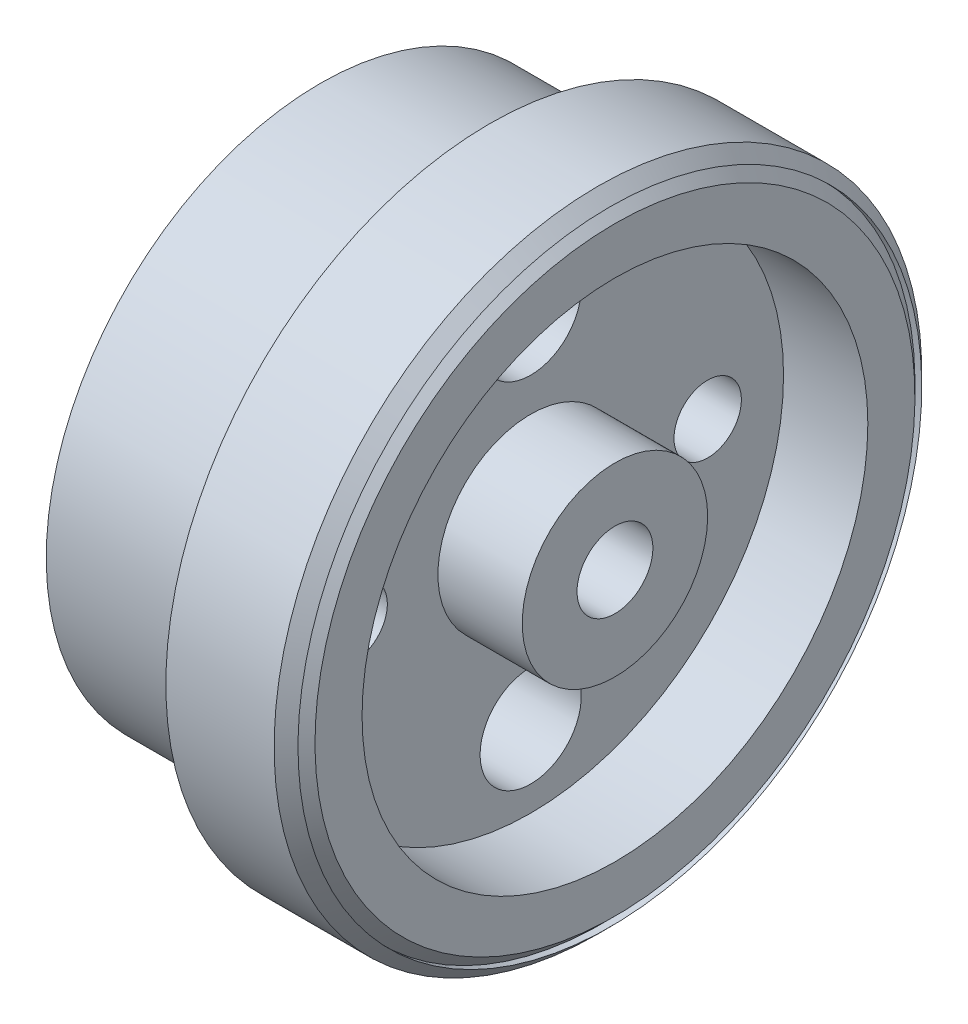
SolidWorks part; units mm, degrees
material "Erable"
ref_plane "Plan de face" through (0, 0, 0) normal (0, 0, 1) x (1, 0, 0)
ref_plane "Plan de dessus" through (0, 0, 0) normal (0, 1, 0) x (1, 0, 0)
ref_plane "Plan de droite" through (0, 0, 0) normal (1, 0, 0) x (0, 0, -1)
sketch "Esquisse1" plane through (0, 0, 0) normal (0, 0, 1) x (1, 0, 0)
  line L0 (0, 0) -> (-42.1873, 0) construction
  line L2 (-0.6031, -37) -> (-1.4142, -37)
  line L40 (-1.4142, -37) -> (0, -35.5858)
  line L55 (-0.6031, -37) -> (-2.0173, -38.4142)
  line L56 (-2.0173, -38.4142) -> (-14.8625, -38.4142)
  line L57 (-14.8625, -38.4142) -> (-15.958, -36.7409)
  line L82 (0, -4.5) -> (0, -35.5858)
  line L83 (-15.958, -36.7409) -> (-15.958, -32.5076)
  line L84 (-15.958, -32.5076) -> (-34.958, -32.5076)
  line L85 (-34.958, -32.5076) -> (-34.958, -27.5104)
  line L89 (-34.958, -15.3377) -> (-34.958, -11.0143)
  line L90 (-34.958, -11.0143) -> (-36.958, -11.0143)
  line L91 (-36.958, -11.0143) -> (-36.958, -11)
  line L92 (-36.958, -11) -> (-44.958, -11)
  line L94 (-14.8625, -38.4142) -> (-14.8625, -28.5496) construction
  line L96 (-34.958, -27.5104) -> (-34.958, -15.3377)
  line L103 (-43.429, -7.5149) -> (-44.958, -8.8042)
  line L104 (-44.958, -8.8042) -> (-44.958, -11)
  line L105 (-23.429, -7.5149) -> (-20.4142, -4.5)
  line L106 (-43.429, -7.5149) -> (-3.9293, -7.5149) construction
  line L107 (-43.429, -7.5149) -> (-23.429, -7.5149)
  line L108 (0, -4.5) -> (-20.4142, -4.5)
  dimension "D2" = 2
  dimension "D3" = 2
  dimension "D4" = 19
  dimension "D5" = 2
  dimension "D6" = 12.8452
  dimension "D7" = 11
  dimension "D8" = 4.5
  dimension "D9" = 45
  dimension "D10" = 8
  dimension "D11" = 315
  dimension "D12" = 2
  dimension "D13" = 2
  dimension "D14" = 37
  dimension "D15" = 0
  dimension "D16" = 35.5858
  dimension "D17" = 20
revolve "Révolution1" add sketch "Esquisse1" angle 360 about L0
sketch "Esquisse2" plane through (0, 0, 0) normal (1, 0, 0) x (0, 0, -1)
  circle A0 centre (0, 0) radius 30
  circle A2 centre (0, 0) radius 11
extrude "Enlèv. mat.-Extru.2" cut sketch "Esquisse2" against normal blind 10
sketch "Esquisse4" plane through (-10, 0, 0) normal (1, 0, 0) x (0, 0, -1)
  line L0 (0, 0) -> (21, 0) construction
  line L1 (0, 0) -> (0, 20.3179) construction
  circle A0 centre (21, 0) radius 4
  circle A1 centre (-21, 0) radius 4
  dimension "D2" = 8
  dimension "D1" = 21
extrude "Enlèv. mat.-Extru.3" cut sketch "Esquisse4" against normal through all
sketch "Esquisse5" plane through (-10, 0, 0) normal (1, 0, 0) x (0, 0, -1)
  line L0 (0, 4.2151) -> (0, 27.1536) construction
  circle A0 centre (0, 21) radius 6
  dimension "D2" = 12
  dimension "D1" = 21
extrude "Enlèv. mat.-Extru.4" cut sketch "Esquisse5" against normal through all
pattern_circular "Répétition circulaire1" count 2 over 180 about axis through (0, 0, 0) along (1, 0, 0) of "Enlèv. mat.-Extru.4"
